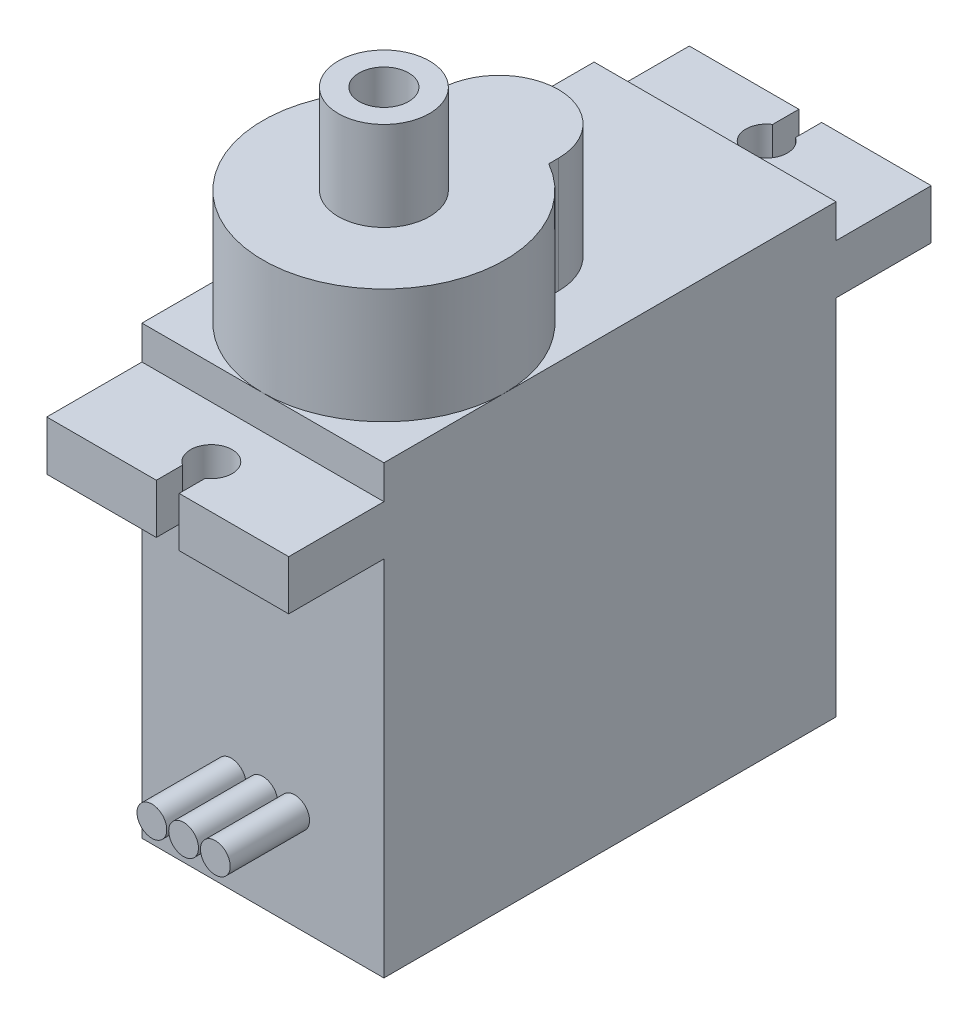
SolidWorks part; units mm, degrees
ref_plane "Front Plane" through (0, 0, 0) normal (0, 0, 1) x (1, 0, 0)
ref_plane "Top Plane" through (0, 0, 0) normal (0, 1, 0) x (1, 0, 0)
ref_plane "Right Plane" through (0, 0, 0) normal (1, 0, 0) x (0, 0, -1)
sketch "Sketch1" plane through (0, 0, 0) normal (1, 0, 0) x (0, 0, -1)
  line L0 (-11.4, -11.25) -> (-11.4, 7.05)
  line L1 (-11.4, 7.05) -> (-16.2, 7.05)
  line L2 (-16.2, 7.05) -> (-16.2, 9.55)
  line L3 (-16.2, 9.55) -> (-11.4, 9.55)
  line L4 (-11.4, 9.55) -> (-11.4, 11.25)
  line L5 (-11.4, 11.25) -> (11.4, 11.25)
  line L6 (11.4, 11.25) -> (11.4, 9.55)
  line L7 (11.4, 9.55) -> (16.2, 9.55)
  line L8 (16.2, 9.55) -> (16.2, 7.05)
  line L9 (16.2, 7.05) -> (11.4, 7.05)
  line L10 (11.4, 7.05) -> (11.4, -11.25)
  line L11 (11.4, -11.25) -> (-11.4, -11.25)
  line L12 (0, -11.25) -> (0, 11.25) construction
  point P15 (0, 0)
  dimension "D1" = 22.8
  dimension "D2" = 18.3
  dimension "D3" = 2.5
  dimension "D4" = 4.8
  dimension "D5" = 22.5
extrude "Boss-Extrude1" add sketch "Sketch1" along normal blind 12.2
sketch "Sketch2" plane through (0, 11.25, 0) normal (0, 1, 0) x (1, 0, 0)
  line L2 (12.2, 11.4) -> (12.2, -11.4) construction
  line L3 (12.2, -11.4) -> (0, -11.4) construction
  line L4 (12.2, -11.4) -> (0, -11.4) construction
  circle A0 centre (6.1, -5.3) radius 6.1
  point P8 (6.1, -11.4)
extrude "Boss-Extrude2" add sketch "Sketch2" along normal blind 5.8
sketch "Sketch3" plane through (0, 17.05, 0) normal (0, 1, 0) x (1, 0, 0)
  circle A38 centre (6.1, -5.3) radius 2.3
  dimension "D1" = 4.6
sketch "Sketch4" plane through (0, 11.25, 0) normal (0, 1, 0) x (1, 0, 0)
  line L1 (3.1, 0.5) -> (3.1, 0.0113)
  line L2 (9.1, 0.5) -> (9.1, 0.0113)
  line L4 (12.2, -11.4) -> (0, -11.4) construction
  arc A2 (12.2, -5.3) -> (0, -5.3) centre (6.1, -5.3) ccw construction
  arc A4 (9.1, 0.0113) -> (3.1, 0.0113) centre (6.1, -5.3) ccw
  arc A5 (3.1, 0.5) -> (9.1, 0.5) centre (6.1, 0.5) cw
  point P5 (6.1, 3.5)
  point P15 (6.1, -11.4)
  dimension "D1" = 6
  dimension "D2" = 14.9
extrude "Boss.-Extru.1" add sketch "Sketch4" along normal up to surface (5.8 mm away) up to face at (6.1, 17.05, 11.4)
sketch "Sketch6" plane through (0, 9.55, 0) normal (0, 1, 0) x (1, 0, 0)
  line L0 (5.525, 14.8786) -> (6.675, 14.8786) construction
  line L1 (0, 0) -> (-2.246, 0) construction
  line L2 (5.525, -16.2) -> (6.675, -16.2)
  line L3 (12.2, 16.2) -> (0, 16.2) construction
  line L4 (5.525, 14.8786) -> (5.525, 16.2)
  line L5 (6.675, 14.8786) -> (6.675, 16.2)
  line L6 (5.525, 16.2) -> (6.675, 16.2)
  line L7 (6.675, -14.8786) -> (6.675, -16.2)
  line L8 (5.525, -14.8786) -> (5.525, -16.2)
  arc A1 (5.525, 14.8786) -> (6.675, 14.8786) centre (6.1, 14) ccw
  arc A2 (5.525, -14.8786) -> (6.675, -14.8786) centre (6.1, -14) cw
  point P4 (6.1, 16.2)
  point P5 (6.1, 16.2)
  point P17 (6.1, 12.95)
  point P18 (6.1, -12.95)
  dimension "D1" = 1.05
  dimension "D2" = 1.15
  dimension "D3" = 25.9
extrude "Enlèv. mat.-Extru.1" cut sketch "Sketch6" against normal through all
sketch "Sketch8" plane through (0, 0, 11.4) normal (0, 0, 1) x (1, 0, 0)
  line L2 (12.2, -11.25) -> (0, -11.25) construction
  circle A3 centre (6.1, -6.25) radius 0.75
  circle A4 centre (7.7, -6.25) radius 0.75
  circle A6 centre (4.5, -6.25) radius 0.75
  circle A7 centre (6.1, -6.25) radius 0.75 [skipped]
  point P4 (6.1, -11.25)
  dimension "D1" = 1.5
  dimension "D2" = 5
  dimension "D3" = 2
  dimension "D4" = 2
extrude "Boss-Extrude5" add sketch "Sketch8" along normal blind 4
extrude "Boss-Extrude6" add sketch "Sketch3" along normal blind 4.5
hole_wizard "Diamètre du perçage Ø2.5 (2.5)1" positions "Esquisse2" profile "Esquisse1" hole size "Ø2.5" standard "DIN"
sketch "Esquisse2" plane through (0, 21.55, 0) normal (0, 1, 0) x (1, 0, 0)
  point P0 (6.1, -5.3)
sketch "Esquisse1" plane through (6.1, 21.55, 5.3) normal (1, 0, 0) x (0, 0, 1)
  line L0 (0, 0) -> (0, 4.7511)
  line L1 (0, 4.7511) -> (1.25, 4)
  line L2 (1.25, 4) -> (1.25, 0)
  line L5 (1.25, 0) -> (0, 0)
  line L10 (0, 4.7511) -> (-1.25, 4) construction
  line L11 (0, -6.35) -> (0, 107.95) construction
  dimension "Diamètre du perçage" = 2.5
  dimension "Profondeur du perçage" = 4
  dimension "Angle de pointe" = 118
